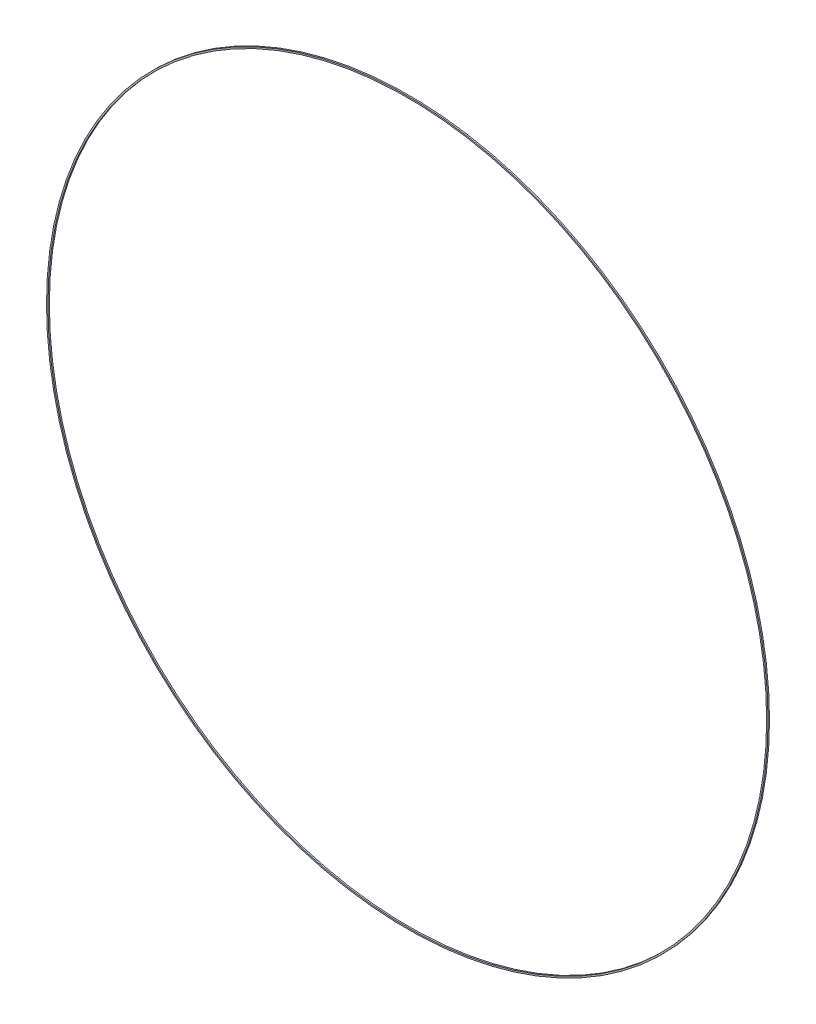
SolidWorks part; units mm, degrees
ref_plane "Front Plane" through (0, 0, 0) normal (0, 0, 1) x (1, 0, 0)
ref_plane "Top Plane" through (0, 0, 0) normal (0, 1, 0) x (1, 0, 0)
ref_plane "Right Plane" through (0, 0, 0) normal (1, 0, 0) x (0, 0, -1)
sketch "Sketch1" plane through (0, 0, 0) normal (0, 0, 1) x (1, 0, 0)
  line L0 (0, 0) -> (0, -500.5) construction
  circle A0 centre (0, -500.5) radius 500.5
  circle A1 centre (0, -500.5) radius 498.5
  dimension "D1" = 1001
  dimension "D2" = 2
extrude "Boss-Extrude1" add sketch "Sketch1" along normal blind 2
